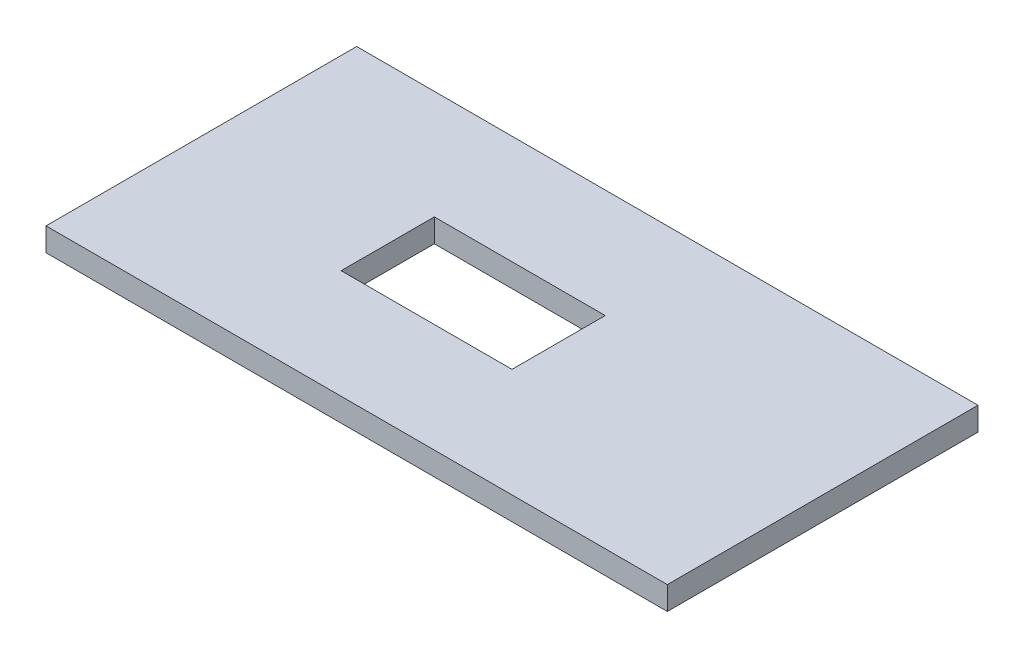
SolidWorks part; units mm, degrees
ref_plane "Front Plane" through (0, 0, 0) normal (0, 0, 1) x (1, 0, 0)
ref_plane "Top Plane" through (0, 0, 0) normal (0, 1, 0) x (1, 0, 0)
ref_plane "Right Plane" through (0, 0, 0) normal (1, 0, 0) x (0, 0, -1)
sketch "Sketch1" plane through (0, 0, 0) normal (0, 1, 0) x (1, 0, 0)
  line L0 (0, 40) -> (80, 40)
  line L1 (0, 40) -> (0, 0)
  line L2 (0, 0) -> (80, 0)
  line L3 (80, 40) -> (80, 0)
  line L5 (24, 26) -> (46, 26)
  line L6 (24, 26) -> (24, 14)
  line L7 (24, 14) -> (46, 14)
  line L8 (46, 26) -> (46, 14)
  dimension "D1" = 80
  dimension "D2" = 40
  dimension "D3" = 12
  dimension "D4" = 22
  dimension "D5" = 24
  dimension "D6" = 14
extrude "Boss-Extrude1" add sketch "Sketch1" along normal blind 3
